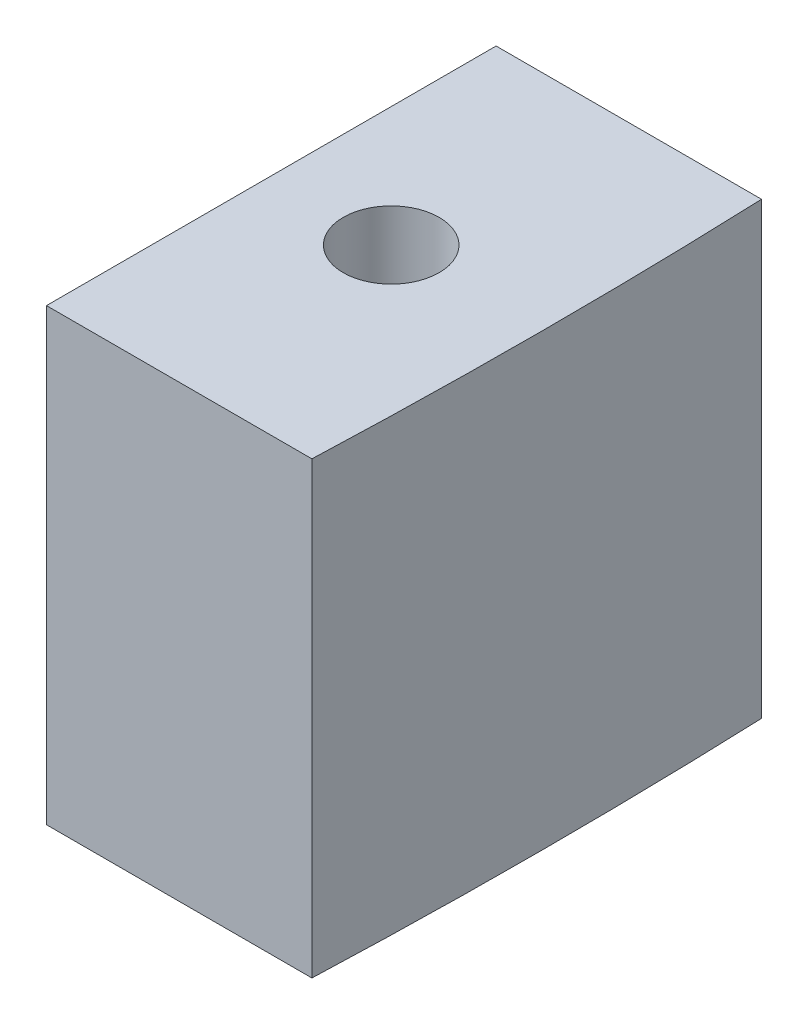
SolidWorks part; units mm, degrees
ref_plane "前视基准面" through (0, 0, 0) normal (0, 0, 1) x (1, 0, 0)
ref_plane "上视基准面" through (0, 0, 0) normal (0, 1, 0) x (1, 0, 0)
ref_plane "右视基准面" through (0, 0, 0) normal (1, 0, 0) x (0, 0, -1)
sketch "草图1" plane through (0, 0, 0) normal (0, 1, 0) x (1, 0, 0)
  line L1 (-33.4485, 7.5) -> (33.4485, 7.5)
  line L2 (-33.4485, 7.5) -> (-33.4485, -7.5)
  line L3 (-33.4485, -7.5) -> (33.4485, -7.5)
  line L4 (33.4485, 7.5) -> (33.4485, -7.5)
  line L5 (-33.4485, 7.5) -> (33.4485, -7.5) construction
  line L6 (-33.4485, -7.5) -> (33.4485, 7.5) construction
  point P0 (0, 0)
  dimension "D1" = 15
extrude "凸台-拉伸1" add sketch "草图1" along normal blind 15
sketch "草图2" plane through (0, 0, 0) normal (0, -1, 0) x (1, 0, 0)
  line L0 (-24.5936, 7.5) -> (33.4485, 7.5)
  line L1 (33.4485, 7.5) -> (33.4485, -7.5)
  line L2 (33.4485, -7.5) -> (-24.5936, -7.5)
  line L5 (33.4485, -7.5) -> (-33.4485, -7.5) construction
  line L6 (-33.4485, 7.5) -> (33.4485, 7.5) construction
  arc A0 (-24.5936, -7.5) -> (-24.5936, 7.5) centre (-218.4485, 0) ccw
  point P2 (0, 0)
  point P10 (0, 0)
  point P13 (0, 0)
extrude "切除-拉伸1" cut sketch "草图2" against normal up to next
hole_wizard "M3 间隙孔1" positions "草图3" profile "草图4" hole size "M3" standard "ISO" end condition up to next
sketch "草图3" plane through (0, 0, 0) normal (0, -1, 0) x (-1, 0, 0)
  line L1 (-4.95, 0) -> (4.95, 0) construction
  line L2 (33.4485, 7.5) -> (33.4485, -7.5) construction
  point P0 (29.4485, 0)
  point P3 (0, 0)
  dimension "D1" = 4
sketch "草图4" plane through (-29.4485, 0, 0) normal (1, 0, 0) x (0, 0, -1)
  line L0 (0, 0) -> (0, 15)
  line L1 (0, 15) -> (1.6, 15)
  line L2 (1.6, 15) -> (1.6, 0)
  line L5 (1.6, 0) -> (0, 0)
  line L11 (0, -6.35) -> (0, 107.95) construction
  dimension "通孔孔直径" = 3.2
  dimension "通孔孔深度" = 15
sketch "草图5" plane through (0, 0, 0) normal (0, -1, 0) x (1, 0, 0)
  line L1 (-29.4485, -3.2332) -> (-26.6485, -1.6166)
  line L2 (-26.6485, -1.6166) -> (-26.6485, 1.6166)
  line L3 (-26.6485, 1.6166) -> (-29.4485, 3.2332)
  line L4 (-29.4485, 3.2332) -> (-32.2485, 1.6166)
  line L5 (-32.2485, 1.6166) -> (-32.2485, -1.6166)
  line L6 (-32.2485, -1.6166) -> (-29.4485, -3.2332)
  circle A0 centre (-29.4485, 0) radius 2.8 construction
  point P1 (0, 0)
  point P9 (0, 0)
extrude "切除-拉伸2" cut sketch "草图5" against normal blind 4
